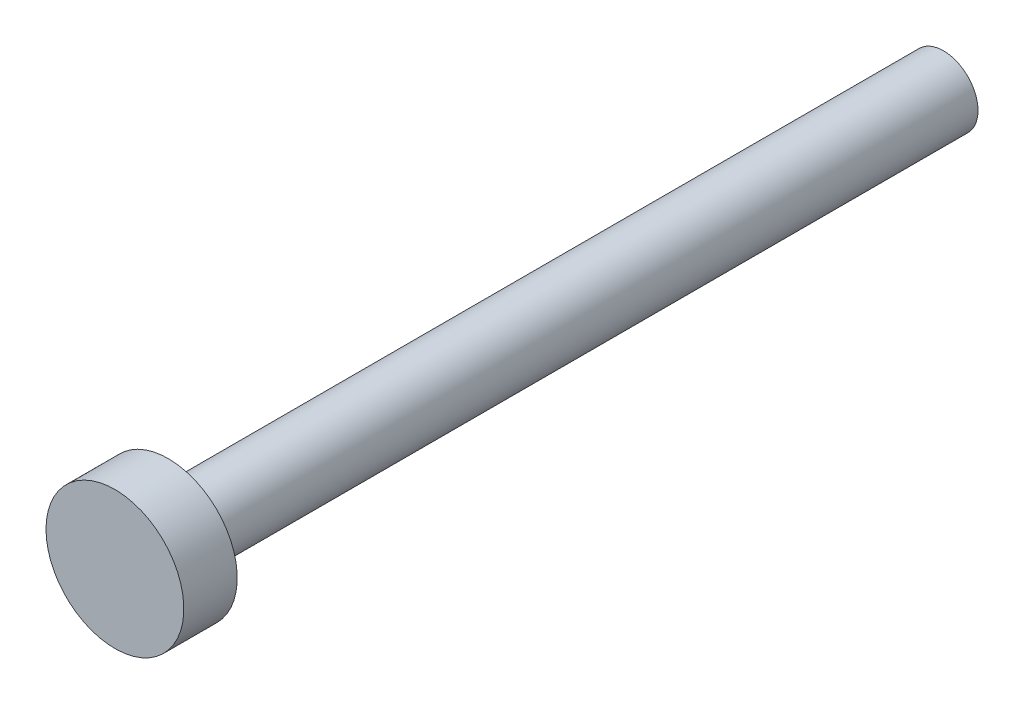
SolidWorks part; units mm, degrees
ref_plane "Plan de face" through (0, 0, 0) normal (0, 0, 1) x (1, 0, 0)
ref_plane "Plan de dessus" through (0, 0, 0) normal (0, 1, 0) x (1, 0, 0)
ref_plane "Plan de droite" through (0, 0, 0) normal (1, 0, 0) x (0, 0, -1)
sketch "Esquisse1" plane through (0, 0, 0) normal (0, 0, 1) x (1, 0, 0)
  circle A0 centre (0, 0) radius 4
  dimension "D1" = 8
extrude "Boss.-Extru.1" add sketch "Esquisse1" along normal blind 3.1
sketch "Esquisse2" plane through (0, 0, 0) normal (0, 0, -1) x (-1, 0, 0)
  circle A0 centre (0, 0) radius 2
  dimension "D1" = 4
extrude "Boss.-Extru.2" add sketch "Esquisse2" along normal blind 45
